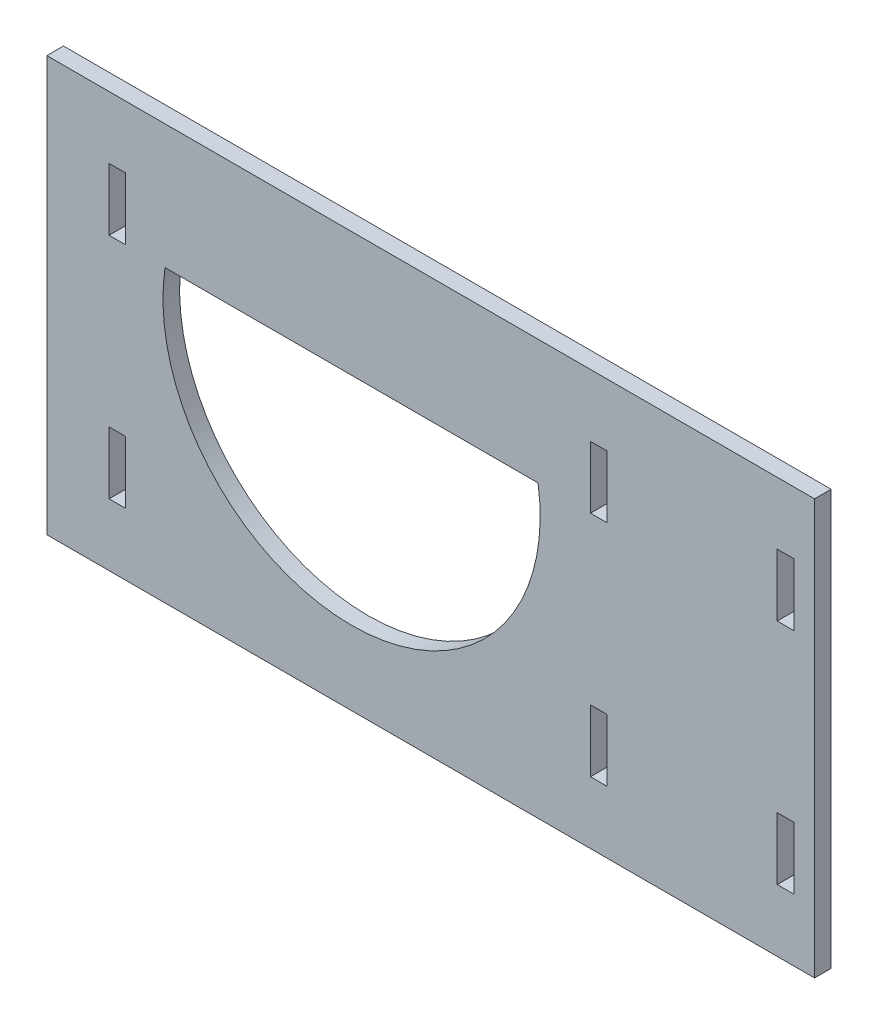
SolidWorks part; units mm, degrees
ref_plane "Front Plane" through (0, 0, 0) normal (0, 0, 1) x (1, 0, 0)
ref_plane "Top Plane" through (0, 0, 0) normal (0, 1, 0) x (1, 0, 0)
ref_plane "Right Plane" through (0, 0, 0) normal (1, 0, 0) x (0, 0, -1)
sketch "Sketch1" plane through (0, 0, 0) normal (0, 0, 1) x (1, 0, 0)
  line L0 (-46.5163, 20) -> (43.375, 20)
  line L1 (-75, -50) -> (75, -50)
  line L3 (-75, 50) -> (75, 50)
  line L5 (-75, -50) -> (75, 50) construction
  line L6 (-75, 50) -> (75, -50) construction
  line L21 (0, 80.4433) -> (0, -75.6846) construction
  line L22 (56, 35) -> (60, 35)
  line L23 (56, 35) -> (56, 20)
  line L24 (56, 20) -> (60, 20)
  line L25 (60, 35) -> (60, 20)
  line L26 (-110.7456, 0) -> (128.9906, 0) construction
  line L27 (56, -20) -> (60, -20)
  line L28 (56, -35) -> (56, -20)
  line L29 (60, -35) -> (60, -20)
  line L30 (56, -35) -> (60, -35)
  line L31 (-56, -35) -> (-56, -20)
  line L32 (-56, -20) -> (-60, -20)
  line L33 (-60, -35) -> (-60, -20)
  line L34 (-56, -35) -> (-60, -35)
  line L35 (-56, 20) -> (-60, 20)
  line L36 (-56, 35) -> (-56, 20)
  line L37 (-60, 35) -> (-60, 20)
  line L38 (-56, 35) -> (-60, 35)
  line L42 (75, 50) -> (110, 50)
  line L51 (110, 50) -> (110, -50)
  line L52 (110, -50) -> (75, -50)
  line L53 (-75, 50) -> (-75, -50)
  line L54 (105, 35) -> (101, 35)
  line L55 (105, 35) -> (105, 20)
  line L56 (105, 20) -> (101, 20)
  line L57 (101, 35) -> (101, 20)
  line L58 (105, -20) -> (101, -20)
  line L59 (105, -20) -> (105, -35)
  line L60 (105, -35) -> (101, -35)
  line L61 (101, -20) -> (101, -35)
  arc A11 (-46.5163, 20) -> (43.375, 20) centre (-1.5707, 13.2674) ccw
  point P0 (0, 0)
  dimension "D3" = 20
  dimension "D1" = 100
  dimension "D2" = 150
  dimension "D12" = 4
  dimension "D13" = 15
  dimension "D14" = 35
  dimension "D15" = 15
  dimension "D17" = 5
  dimension "D18" = 5
extrude "Boss-Extrude1" add sketch "Sketch1" along normal blind 4
